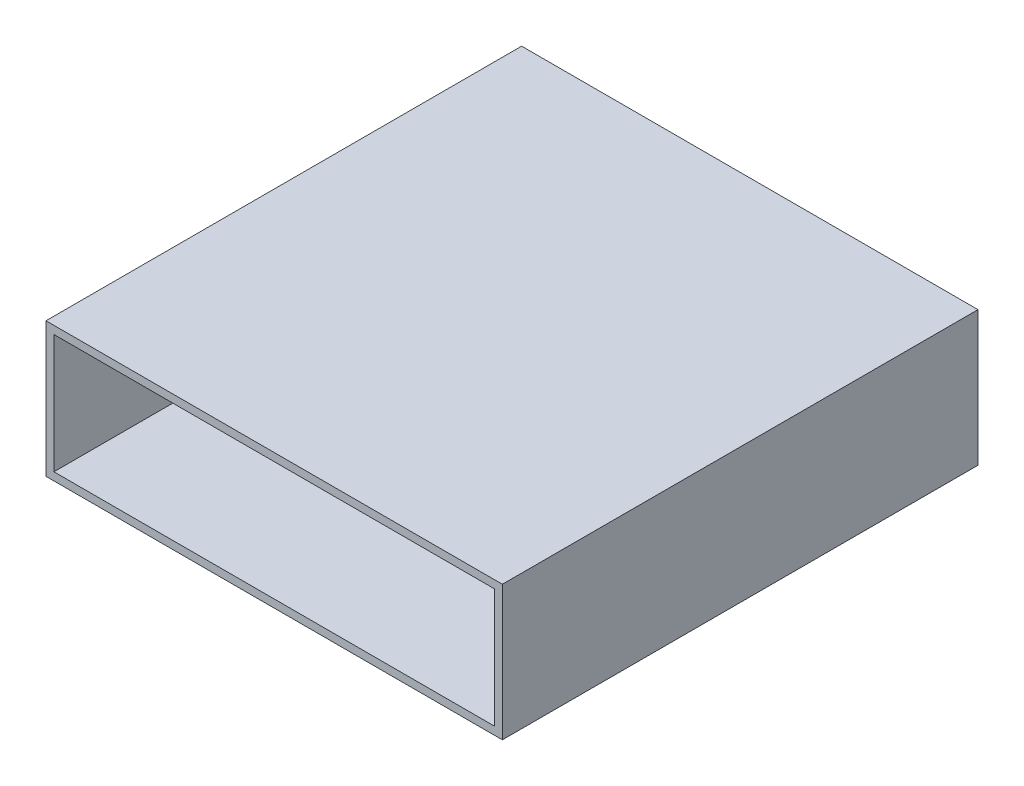
SolidWorks part; units mm, degrees
ref_plane "Front Plane" through (0, 0, 0) normal (0, 0, 1) x (1, 0, 0)
ref_plane "Top Plane" through (0, 0, 0) normal (0, 1, 0) x (1, 0, 0)
ref_plane "Right Plane" through (0, 0, 0) normal (1, 0, 0) x (0, 0, -1)
sketch "Sketch1" plane through (0, 0, 0) normal (0, 0, 1) x (1, 0, 0)
  line L1 (0, 0) -> (-115.14, 0)
  line L2 (0, 0) -> (0, 34)
  line L3 (0, 34) -> (-115.14, 34)
  line L4 (-115.14, 0) -> (-115.14, 34)
  dimension "D1" = 115.14
  dimension "D2" = 34
extrude "Boss-Extrude1" add sketch "Sketch1" along normal blind 120
sketch "Sketch2" plane through (0, 0, 120) normal (0, 0, 1) x (1, 0, 0)
  line L0 (0, 34) -> (-115.14, 34) construction
  line L1 (-113.14, 32) -> (-2, 32)
  line L2 (-113.14, 32) -> (-113.14, 2)
  line L3 (-113.14, 2) -> (-2, 2)
  line L4 (-2, 32) -> (-2, 2)
  line L5 (-115.14, 34) -> (-115.14, 0) construction
  line L6 (-115.14, 0) -> (0, 0) construction
  line L7 (0, 0) -> (0, 34) construction
  dimension "D1" = 2
  dimension "D2" = 2
  dimension "D3" = 2
  dimension "D4" = 2
extrude "Cut-Extrude1" cut sketch "Sketch2" against normal blind 116
sketch "Sketch3" plane through (0, 0, 0) normal (0, 0, -1) x (-1, 0, 0)
  line L0 (0, 34) -> (115.14, 34) construction
  line L1 (2, 32) -> (113.14, 32)
  line L2 (2, 32) -> (2, 2)
  line L3 (2, 2) -> (113.14, 2)
  line L4 (113.14, 32) -> (113.14, 2)
  line L5 (0, 0) -> (0, 34) construction
  line L6 (115.14, 0) -> (0, 0) construction
  line L7 (115.14, 34) -> (115.14, 0) construction
  dimension "D1" = 2
  dimension "D2" = 2
  dimension "D3" = 2
  dimension "D4" = 2
extrude "Cut-Extrude2" cut sketch "Sketch3" against normal blind 2
